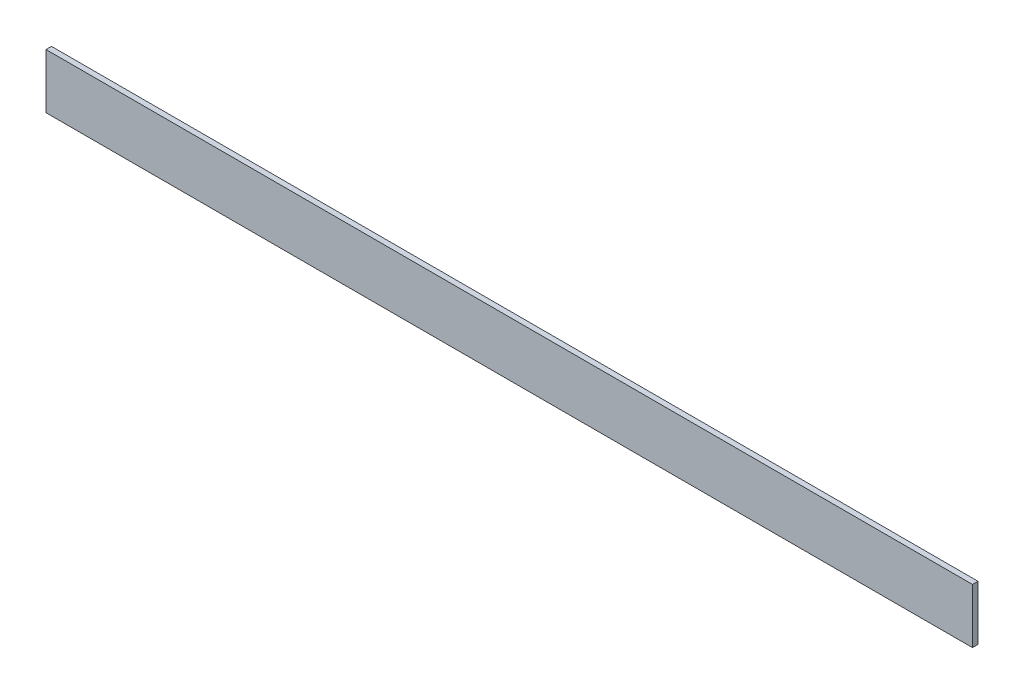
SolidWorks part; units mm, degrees
ref_plane "Front Plane" through (0, 0, 0) normal (0, 0, 1) x (1, 0, 0)
ref_plane "Top Plane" through (0, 0, 0) normal (0, 1, 0) x (1, 0, 0)
ref_plane "Right Plane" through (0, 0, 0) normal (1, 0, 0) x (0, 0, -1)
sketch "Sketch1" plane through (0, 0, 0) normal (0, 0, 1) x (1, 0, 0)
  line L1 (0, 0) -> (177.8, 0)
  line L2 (0, 0) -> (0, 10.5029)
  line L3 (0, 10.5029) -> (177.8, 10.5029)
  line L4 (177.8, 0) -> (177.8, 10.5029)
  dimension "D1" = 177.8
  dimension "D2" = 10.5029
extrude "Boss-Extrude1" add sketch "Sketch1" along normal blind 1.0541
